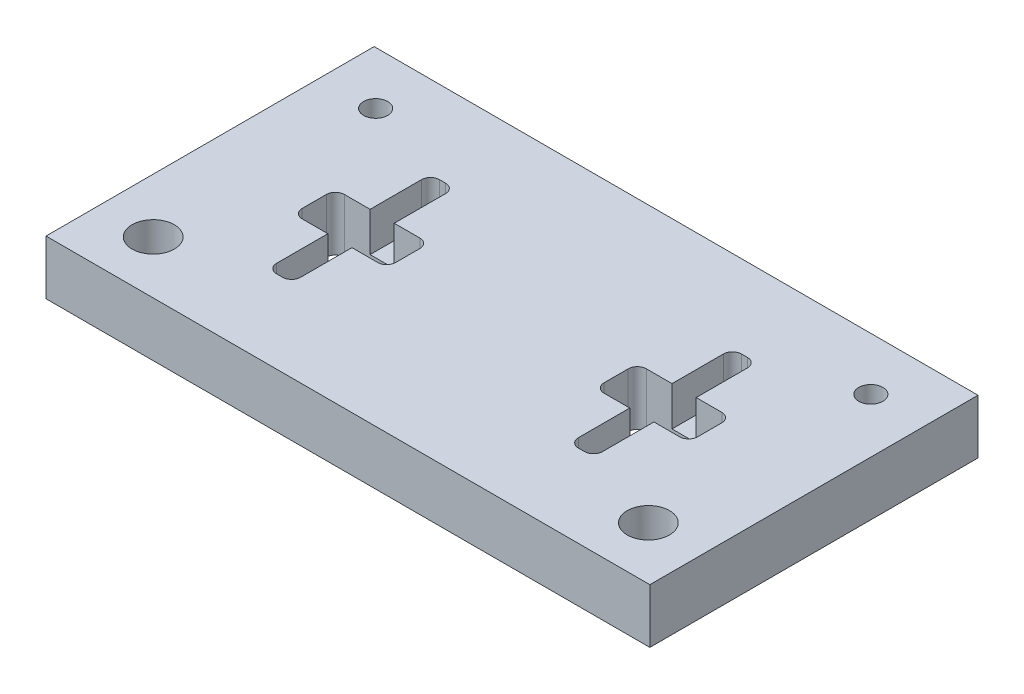
SolidWorks part; units mm, degrees
material "Plain Carbon Steel"
ref_plane "Front Plane" through (0, 0, 0) normal (0, 0, 1) x (1, 0, 0)
ref_plane "Top Plane" through (0, 0, 0) normal (0, 1, 0) x (1, 0, 0)
ref_plane "Right Plane" through (0, 0, 0) normal (1, 0, 0) x (0, 0, -1)
sketch "Sketch1" plane through (0, 0, 0) normal (0, 1, 0) x (1, 0, 0)
  line L1 (0, 0) -> (200, 0)
  line L2 (0, 0) -> (0, -108.68)
  line L3 (0, -108.68) -> (200, -108.68)
  line L4 (200, 0) -> (200, -108.68)
  dimension "D1" = 108.68
  dimension "D2" = 200
extrude "Boss-Extrude1" add sketch "Sketch1" along normal blind 18
sketch "Sketch2" plane through (0, 18, 0) normal (0, 1, 0) x (1, 0, 0)
  line L0 (0, 0) -> (0, -108.68) construction
  line L1 (200, 0) -> (0, 0) construction
  line L2 (100, 0) -> (100, -108.68) construction
  line L3 (0, -108.68) -> (200, -108.68) construction
  line L4 (0, -54.34) -> (200, -54.34) construction
  line L5 (200, -108.68) -> (200, 0) construction
  line L6 (134.5, -47.34) -> (134.5, -61.34)
  line L7 (34.5, -47.34) -> (65.5, -47.34)
  line L8 (34.5, -47.34) -> (34.5, -61.34)
  line L9 (34.5, -61.34) -> (65.5, -61.34)
  line L10 (65.5, -47.34) -> (65.5, -61.34)
  line L11 (165.5, -61.34) -> (134.5, -61.34)
  line L12 (165.5, -47.34) -> (165.5, -61.34)
  line L13 (165.5, -47.34) -> (134.5, -47.34)
  line L14 (0, -29.64) -> (200, -29.64) construction
  line L15 (0, -79.04) -> (200, -79.04) construction
  line L16 (50, -47.34) -> (50, -61.34) construction
  circle A0 centre (18, -17.5) radius 4
  circle A1 centre (182, -17.5) radius 4
  circle A2 centre (18, -91.18) radius 7
  circle A3 centre (182, -91.18) radius 7
  circle A4 centre (18, -17.5) radius 12 construction
  circle A5 centre (182, -17.5) radius 12 construction
  circle A6 centre (18, -91.18) radius 12 construction
  circle A7 centre (182, -91.18) radius 12 construction
  point P20 (34.5, -54.34)
  dimension "D3" = 8
  dimension "D6" = 14
  dimension "D11" = 24
  dimension "D12" = 24
  dimension "D1" = 18
  dimension "D2" = 17.5
  dimension "D4" = 17.5
  dimension "D5" = 18
  dimension "D7" = 31
  dimension "D8" = 14
  dimension "D9" = 50
  dimension "D10" = 24.7
extrude "Cut-Extrude1" cut sketch "Sketch2" against normal blind 30
sketch "Sketch3" plane through (0, 18, 0) normal (0, 1, 0) x (1, 0, 0)
  line L0 (150, -47.34) -> (150, 0) construction
  line L3 (50, -47.34) -> (50, 0) construction
  line L5 (65.5, -47.34) -> (34.5, -47.34) construction
  line L6 (200, 0) -> (0, 0) construction
  line L7 (50, -61.34) -> (50, -108.68) construction
  line L8 (34.5, -61.34) -> (65.5, -61.34) construction
  line L9 (0, -108.68) -> (200, -108.68) construction
  line L10 (165.5, -47.34) -> (134.5, -47.34) construction
  line L11 (150, -61.34) -> (150, -108.68) construction
  line L12 (134.5, -61.34) -> (165.5, -61.34) construction
  line L13 (34.5, -54.34) -> (65.5, -54.34) construction
  line L14 (46, -47.34) -> (54, -47.34)
  line L15 (46, -47.34) -> (46, -27.34)
  line L16 (46, -27.34) -> (54, -27.34)
  line L17 (54, -47.34) -> (54, -27.34)
  line L18 (34.5, -47.34) -> (34.5, -61.34) construction
  line L19 (65.5, -61.34) -> (65.5, -47.34) construction
  line L20 (46, -61.34) -> (54, -61.34)
  line L21 (54, -61.34) -> (54, -81.34)
  line L22 (46, -81.34) -> (54, -81.34)
  line L23 (46, -61.34) -> (46, -81.34)
  line L24 (100, 0) -> (100, -108.68) construction
  line L25 (154, -81.34) -> (146, -81.34)
  line L26 (154, -61.34) -> (154, -81.34)
  line L27 (154, -61.34) -> (146, -61.34)
  line L28 (146, -61.34) -> (146, -81.34)
  line L29 (146, -47.34) -> (146, -27.34)
  line L30 (154, -47.34) -> (146, -47.34)
  line L31 (154, -27.34) -> (146, -27.34)
  line L32 (154, -47.34) -> (154, -27.34)
  point P24 (50, -27.34)
  dimension "D1" = 20
  dimension "D2" = 8
extrude "Cut-Extrude2" cut sketch "Sketch3" against normal blind 13
fillet "Fillet1" radius 3 16 edges at (65.5, 9, 61.34) (65.5, 9, 47.34) (34.5, 9, 47.34) (34.5, 9, 61.34) (165.5, 9, 61.34) (165.5, 9, 47.34) (134.5, 9, 47.34) (134.5, 9, 61.34) (154, 11.5, 81.34) (146, 11.5, 81.34) (146, 11.5, 27.34) (154, 11.5, 27.34) (46, 11.5, 81.34) (54, 11.5, 81.34) (54, 11.5, 27.34) (46, 11.5, 27.34)
equation "\"D1@Sketch1\"=49.4*0.6*2+49.4"
equation "\"D7@Sketch2\"=24+2*3.5"
equation "\"D10@Sketch2\"=49.4/2"
